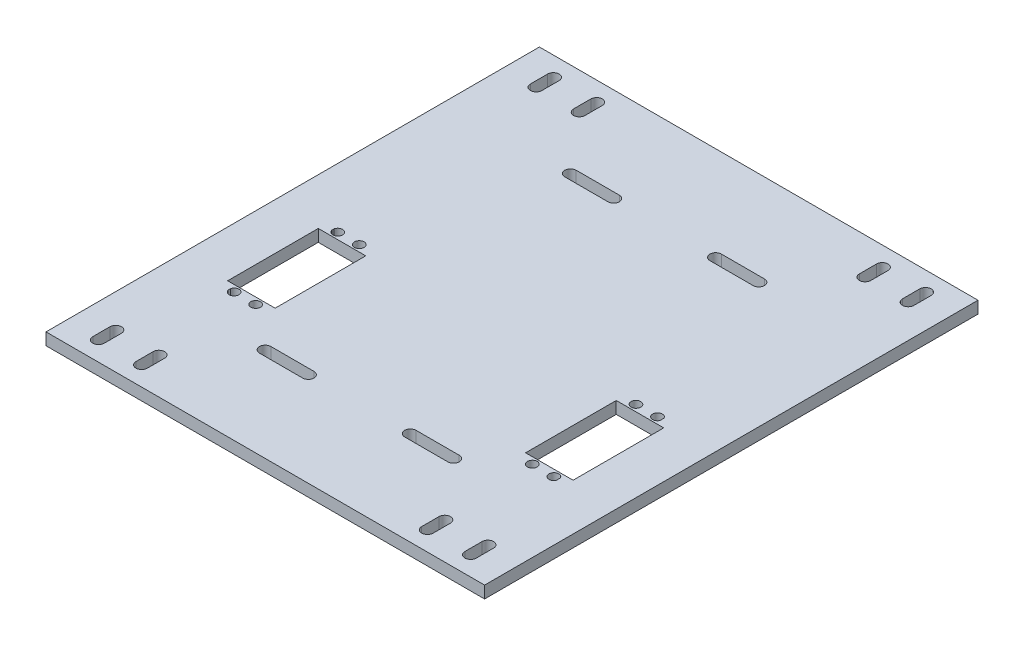
SolidWorks part; units mm, degrees
ref_plane "Front Plane" through (0, 0, 0) normal (0, 0, 1) x (1, 0, 0)
ref_plane "Top Plane" through (0, 0, 0) normal (0, 1, 0) x (1, 0, 0)
ref_plane "Right Plane" through (0, 0, 0) normal (1, 0, 0) x (0, 0, -1)
sketch "Sketch1" plane through (0, 0, 0) normal (0, 1, 0) x (1, 0, 0)
  line L1 (-76.2, -114.3) -> (76.2, -114.3)
  line L2 (-76.2, -114.3) -> (-76.2, 114.3)
  line L3 (-76.2, 114.3) -> (76.2, 114.3)
  line L4 (76.2, -114.3) -> (76.2, 114.3)
  line L5 (-76.2, -114.3) -> (76.2, 114.3) construction
  line L6 (-76.2, 114.3) -> (76.2, -114.3) construction
  point P0 (0, 0)
  dimension "D1" = 152.4
  dimension "D2" = 228.6
extrude "Boss-Extrude1" add sketch "Sketch1" along normal blind 5.588
sketch "Sketch5" plane through (0, 5.588, 0) normal (0, 1, 0) x (1, 0, 0)
  line L0 (76.2, 114.3) -> (-76.2, 114.3) construction
  line L1 (-76.2, 114.3) -> (-76.2, -114.3) construction
  circle A1 centre (0.0606, 19.4827) radius 40 construction
  dimension "D1" = 94.8173
  dimension "D2" = 76.2606
sketch "Sketch2" plane through (0, 5.588, 0) normal (0, 1, 0) x (1, 0, 0)
  line L0 (0.0606, 19.4827) -> (0.0606, -66.1832) construction
  line L1 (69.1452, -20.8673) -> (69.1452, -30.7273) construction
  line L2 (64.1452, -54.7273) -> (74.1452, -54.7273) construction
  line L3 (64.1452, -54.7273) -> (64.1452, -6.7273) construction
  line L4 (64.1452, -6.7273) -> (74.1452, -6.7273) construction
  line L5 (74.1452, -54.7273) -> (74.1452, -6.7273) construction
  line L6 (64.1452, -54.7273) -> (74.1452, -6.7273) construction
  line L7 (64.1452, -6.7273) -> (74.1452, -54.7273) construction
  line L8 (0.0606, 19.4827) -> (65.8816, 19.4827) construction
  line L9 (-58.0239, -9.7273) -> (-80.0239, -51.7273) construction
  line L10 (-58.0239, -51.7273) -> (-80.0239, -9.7273) construction
  line L12 (58.1452, -51.7273) -> (80.1452, -51.7273)
  line L13 (58.1452, -51.7273) -> (58.1452, -9.7273)
  line L14 (58.1452, -9.7273) -> (80.1452, -9.7273)
  line L15 (80.1452, -51.7273) -> (80.1452, -9.7273)
  line L16 (58.1452, -51.7273) -> (80.1452, -9.7273) construction
  line L17 (58.1452, -9.7273) -> (80.1452, -51.7273) construction
  line L18 (-64.0239, -6.7273) -> (-74.0239, -54.7273) construction
  line L19 (-64.0239, -54.7273) -> (-74.0239, -6.7273) construction
  line L20 (-74.0239, -54.7273) -> (-74.0239, -6.7273) construction
  line L21 (-64.0239, -6.7273) -> (-74.0239, -6.7273) construction
  line L22 (-64.0239, -54.7273) -> (-64.0239, -6.7273) construction
  line L23 (-64.0239, -54.7273) -> (-74.0239, -54.7273) construction
  line L24 (-69.0239, -20.8673) -> (-69.0239, -30.7273) construction
  line L25 (-80.0239, -51.7273) -> (-80.0239, -9.7273)
  line L26 (-58.0239, -9.7273) -> (-80.0239, -9.7273)
  line L27 (-58.0239, -51.7273) -> (-58.0239, -9.7273)
  line L28 (-58.0239, -51.7273) -> (-80.0239, -51.7273)
  circle A1 centre (69.1452, -20.8673) radius 40.005 construction
  circle A2 centre (64.1452, -6.7273) radius 2.25
  circle A3 centre (74.1452, -6.7273) radius 2.25
  circle A4 centre (64.1452, -54.7273) radius 2.25
  circle A5 centre (74.1452, -54.7273) radius 2.25
  circle A10 centre (0.0606, 19.4827) radius 40 construction
  circle A11 centre (0.0606, 19.4827) radius 40 construction
  circle A12 centre (-69.0239, -20.8673) radius 40.005 construction
  circle A13 centre (-74.0239, -54.7273) radius 2.25
  circle A14 centre (-64.0239, -54.7273) radius 2.25
  circle A15 centre (-74.0239, -6.7273) radius 2.25
  circle A16 centre (-64.0239, -6.7273) radius 2.25
  point P5 (69.1452, -30.7273)
  point P36 (-69.0239, -30.7273)
  dimension "D1" = 29.21
  dimension "D2" = 80.01
  dimension "D6" = 4.5
  dimension "D3" = 9.86
  dimension "D4" = 48
  dimension "D5" = 10
  dimension "D7" = 42
  dimension "D8" = 22
extrude "Cut-Extrude1" cut sketch "Sketch2" against normal through all
extrude "Cut-Extrude2" cut sketch "Sketch6" against normal through all
sketch "Sketch6" plane through (-338.2002, 5.588, 0) normal (0, 1, 0) x (1, 0, 0)
  circle A1 centre (404.4002, 104.3) radius 2.65
sketch "Sketch7" plane through (0, 5.588, 0) normal (0, 1, 0) x (1, 0, 0)
  line L0 (66.2, 104.3) -> (66.2, 88.8868) construction
  line L1 (66.2, 105.3777) -> (66.2, 97.3777) construction
  line L2 (68.85, 105.3777) -> (68.85, 97.3777)
  line L3 (63.55, 105.3777) -> (63.55, 97.3777)
  arc A0 (68.85, 105.3777) -> (63.55, 105.3777) centre (66.2, 105.3777) ccw
  arc A1 (63.55, 97.3777) -> (68.85, 97.3777) centre (66.2, 97.3777) ccw
  circle A2 centre (66.2, 104.3) radius 2.65 construction
  point P5 (66.2, 101.3777)
  point P12 (66.2, 101.3777)
  dimension "D1" = 8
extrude "Cut-Extrude3" cut sketch "Sketch7" against normal through all
mirror "Mirror1" about plane through (0, 0, 0) normal (0, 0, 1) of "Cut-Extrude3" second plane through (0, 0, 0) second plane normal (1, 0, 0)
extrude "Cut-Extrude4" cut sketch "Sketch8" against normal through all
sketch "Sketch8" plane through (-338.2002, 5.588, 0) normal (0, 1, 0) x (1, 0, 0)
  circle A1 centre (381.8283, 70.7262) radius 2.65
sketch "Sketch9" plane through (0, 5.588, 0) normal (0, 1, 0) x (1, 0, 0)
  line L0 (43.6281, 70.7262) -> (22.9864, 70.7262) construction
  line L1 (43.6281, 70.7262) -> (23.6281, 70.7262) construction
  line L2 (43.6281, 68.0762) -> (23.6281, 68.0762)
  line L3 (43.6281, 73.3762) -> (23.6281, 73.3762)
  arc A0 (43.6281, 68.0762) -> (43.6281, 73.3762) centre (43.6281, 70.7262) ccw
  arc A1 (23.6281, 73.3762) -> (23.6281, 68.0762) centre (23.6281, 70.7262) ccw
  circle A2 centre (43.6281, 70.7262) radius 2.65 construction
  point P3 (33.6281, 70.7262)
  dimension "D1" = 20
extrude "Cut-Extrude5" cut sketch "Sketch9" against normal through all
mirror "Mirror2" about plane through (0, 0, 0) normal (0, 0, 1) of "Cut-Extrude5" second plane through (0, 0, 0) second plane normal (1, 0, 0)
sketch "Sketch10" plane through (-76.2, 0, 0) normal (-1, 0, 0) x (0, 0, 1)
  line L1 (-114.3, 5.588) -> (114.3, 5.588)
  line L2 (-114.3, 5.588) -> (-114.3, 0)
  line L3 (-114.3, 0) -> (114.3, 0)
  line L4 (114.3, 5.588) -> (114.3, 0)
extrude "Boss-Extrude2" add sketch "Sketch10" along normal blind 25.4
sketch "Sketch11" plane through (0, 5.588, 0) normal (0, 1, 0) x (1, 0, 0)
  line L0 (-58.0239, -51.7273) -> (-80.0239, -51.7273) construction
  line L1 (-58.0239, -51.7273) -> (-58.0239, -9.7273) construction
  line L2 (-58.0239, -9.7273) -> (-80.0239, -9.7273) construction
  line L3 (-80.0239, -51.7273) -> (-80.0239, -9.7273) construction
  line L4 (-58.0239, -51.7273) -> (-80.0239, -51.7273)
  line L5 (-58.0239, -51.7273) -> (-58.0239, -9.7273)
  line L6 (-58.0239, -9.7273) -> (-80.0239, -9.7273)
  line L7 (-80.0239, -51.7273) -> (-80.0239, -9.7273)
extrude "Cut-Extrude6" cut sketch "Sketch11" against normal through all
mirror "Mirror4" about plane through (0, 0, 0) normal (1, 0, 0) of "Cut-Extrude6", "Boss-Extrude2"
sketch "Sketch12" plane through (0, 5.588, 0) normal (0, 1, 0) x (1, 0, 0)
  line L0 (-76.2, 114.3) -> (-76.2, -114.3) construction
  line L1 (101.6, 114.3) -> (-101.6, 114.3) construction
  line L2 (-101.6, -114.3) -> (101.6, -114.3) construction
  line L3 (-101.6, -114.3) -> (-101.6, 114.3) construction
  line L4 (-63.55, -105.3777) -> (-63.55, -97.3777) construction
  line L5 (-68.85, -97.3777) -> (-68.85, -105.3777) construction
  line L6 (-63.55, -105.3777) -> (-63.55, -97.3777) construction
  line L7 (-68.85, -97.3777) -> (-68.85, -105.3777) construction
  line L8 (-83.55, -97.3777) -> (-83.55, -105.3777)
  line L9 (-88.85, -105.3777) -> (-88.85, -97.3777)
  arc A0 (-63.55, -97.3777) -> (-68.85, -97.3777) centre (-66.2, -97.3777) ccw construction
  arc A1 (-68.85, -105.3777) -> (-63.55, -105.3777) centre (-66.2, -105.3777) ccw construction
  arc A2 (-63.55, -97.3777) -> (-68.85, -97.3777) centre (-66.2, -97.3777) ccw construction
  arc A3 (-68.85, -105.3777) -> (-63.55, -105.3777) centre (-66.2, -105.3777) ccw construction
  arc A4 (-88.85, -97.3777) -> (-83.55, -97.3777) centre (-86.2, -97.3777) cw
  arc A5 (-83.55, -105.3777) -> (-88.85, -105.3777) centre (-86.2, -105.3777) cw
  dimension "D1" = 25.4
extrude "Cut-Extrude7" cut sketch "Sketch12" against normal through all
mirror "Mirror5" about plane through (0, 0, 0) normal (1, 0, 0) of "Cut-Extrude7" second plane through (0, 0, 0) second plane normal (0, 0, 1)
